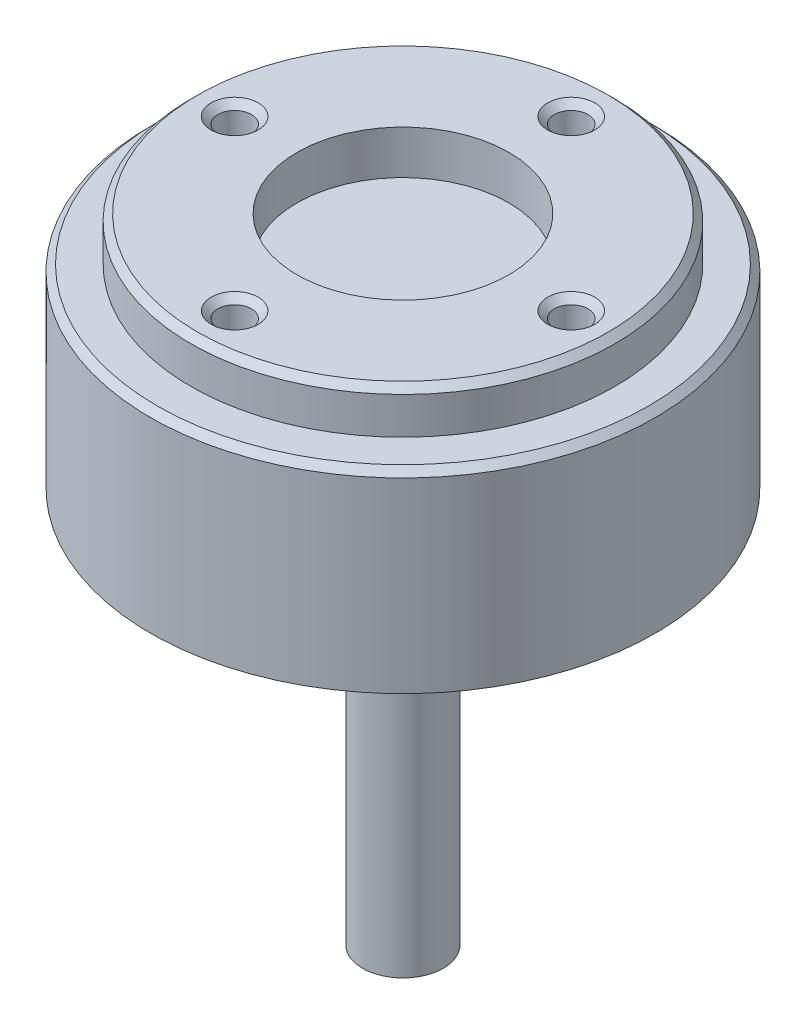
SolidWorks part; units mm, degrees
ref_plane "Front Plane" through (0, 0, 0) normal (0, 0, 1) x (1, 0, 0)
ref_plane "Top Plane" through (0, 0, 0) normal (0, 1, 0) x (1, 0, 0)
ref_plane "Right Plane" through (0, 0, 0) normal (1, 0, 0) x (0, 0, -1)
sketch "Sketch1" plane through (0, 0, 0) normal (0, 1, 0) x (1, 0, 0)
  circle A0 centre (0, 0) radius 37.5
  dimension "D1" = 75
extrude "Boss-Extrude1" add sketch "Sketch1" along normal blind 28.75
sketch "Sketch2" plane through (0, 28.75, 0) normal (0, 1, 0) x (1, 0, 0)
  circle A0 centre (0, 0) radius 31.5
  circle A1 centre (0, 0) radius 15.75
  dimension "D1" = 63
  dimension "D2" = 31.5
extrude "Boss-Extrude2" add sketch "Sketch2" along normal blind 6.5
sketch "Sketch3" plane through (0, 0, 0) normal (0, -1, 0) x (1, 0, 0)
  circle A0 centre (0, 0) radius 6
  dimension "D1" = 12
extrude "Boss-Extrude3" add sketch "Sketch3" along normal blind 58.85
sketch "Sketch4" plane through (0, 0, 0) normal (0, -1, 0) x (1, 0, 0)
  circle A0 centre (0, 0) radius 7.5
  dimension "D1" = 15
extrude "Boss-Extrude4" add sketch "Sketch4" along normal blind 4.7
chamfer "Chamfer1" distance 1 angle 45 2 edges at (0, 35.25, 31.5) (0, 28.75, 37.5)
sketch "Sketch5" plane through (0, 35.25, 0) normal (0, 1, 0) x (1, 0, 0)
  circle A0 centre (0, 25) radius 2.5
  circle A1 centre (0, 0) radius 25 construction
  circle A2 centre (25, 0) radius 2.5
  circle A3 centre (0, -25) radius 2.5
  circle A4 centre (-25, 0) radius 2.5
  point P15 (0, 0)
  dimension "D1" = 5
  dimension "D2" = 50
  dimension "D3" = 4
extrude "Cut-Extrude1" cut sketch "Sketch5" against normal blind 8
chamfer "Chamfer2" distance 1 angle 45 4 edges at (25, 35.25, 2.5) (0, 35.25, 27.5) (-25, 35.25, 2.5) (0, 35.25, -22.5)
